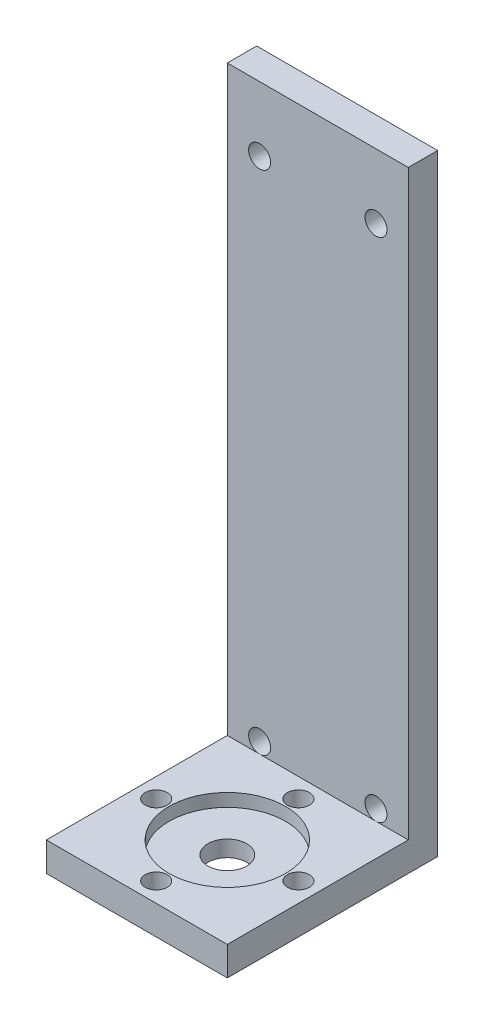
SolidWorks part; units mm, degrees
ref_plane "Front Plane" through (0, 0, 0) normal (0, 0, 1) x (1, 0, 0)
ref_plane "Top Plane" through (0, 0, 0) normal (0, 1, 0) x (1, 0, 0)
ref_plane "Right Plane" through (0, 0, 0) normal (1, 0, 0) x (0, 0, -1)
sketch "Sketch1" plane through (0, 0, 0) normal (0, 1, 0) x (1, 0, 0)
  line L0 (14, 28) -> (14, -7.6379) construction
  line L1 (0, 0) -> (28, 0)
  line L2 (0, 0) -> (0, 28)
  line L3 (0, 28) -> (28, 28)
  line L4 (28, 0) -> (28, 28)
  line L5 (0, 14) -> (47.9207, 14) construction
  circle A0 centre (14, 14) radius 3
  circle A1 centre (14, 25) radius 1.7
  circle A2 centre (25, 14) radius 1.7
  circle A3 centre (14, 3) radius 1.7
  circle A4 centre (3, 14) radius 1.7
  point P11 (14, 7.257)
  dimension "D2" = 6
  dimension "D4" = 3.4
  dimension "D1" = 28
  dimension "D5" = 22
  dimension "D3" = 4
extrude "Boss-Extrude1" add sketch "Sketch1" along normal blind 4.5
sketch "Sketch2" plane through (0, 0, -28) normal (0, 0, -1) x (-1, 0, 0)
  line L1 (-28, 0) -> (0, 0)
  line L2 (-28, 0) -> (-28, 94.6)
  line L3 (-28, 94.6) -> (0, 94.6)
  line L4 (0, 0) -> (0, 94.6)
  dimension "D1" = 94.6
extrude "Boss-Extrude2" add sketch "Sketch2" along normal blind 4.545
sketch "Sketch3" plane through (0, 0, -28) normal (0, 0, 1) x (1, 0, 0)
  line L0 (28, 4.5) -> (0, 4.5) construction
  line L1 (14, 94.6) -> (14, -5.7393) construction
  line L2 (0, 94.6) -> (28, 94.6) construction
  line L3 (28, 49.55) -> (-34.0753, 49.55) construction
  line L4 (28, 94.6) -> (28, 4.5) construction
  circle A0 centre (5, 6.2) radius 1.7
  circle A2 centre (5, 84.6) radius 1.7
  circle A3 centre (23, 6.2) radius 1.7
  circle A4 centre (23, 84.6) radius 1.7
  point P18 (19.5886, 4.2)
  dimension "D1" = 3.4
  dimension "D2" = 10
  dimension "D3" = 5
extrude "Cut-Extrude1" cut sketch "Sketch3" against normal through all
sketch "Sketch5" plane through (0, 4.5, 0) normal (0, 1, 0) x (1, 0, 0)
  circle A0 centre (14, 14) radius 9
  dimension "D1" = 18
extrude "Cut-Extrude2" cut sketch "Sketch5" against normal blind 2
equation "\"F\"= 300'N"
equation "\"h\"= 2.5'mm (base depth)"
equation "\"d\"= 28'mm (base width)"
equation "\"sig\"= 7.78'MPa (stress)"
equation "\"w\"= sqr ( ( \"F\" * \"h\" / 1000 * 6 ) / ( \"d\" / 1000 * \"sig\" * 10 ^ 6 ) )'width (m)"
equation "\"wmm\"= \"w\" * 1000'width(mm)"
equation "\"screw\"= 3.4'mm(screw clearance)"
equation "\"D4@Sketch1\"=\"screw\""
equation "\"D1@Sketch3\"=\"screw\""
equation "\"bossm\"= 2'mm(boss depth)"
equation "\"D1@Cut-Extrude2\"=\"bossm\""
equation "\"D1@Boss-Extrude2\"=\"wmm\""
